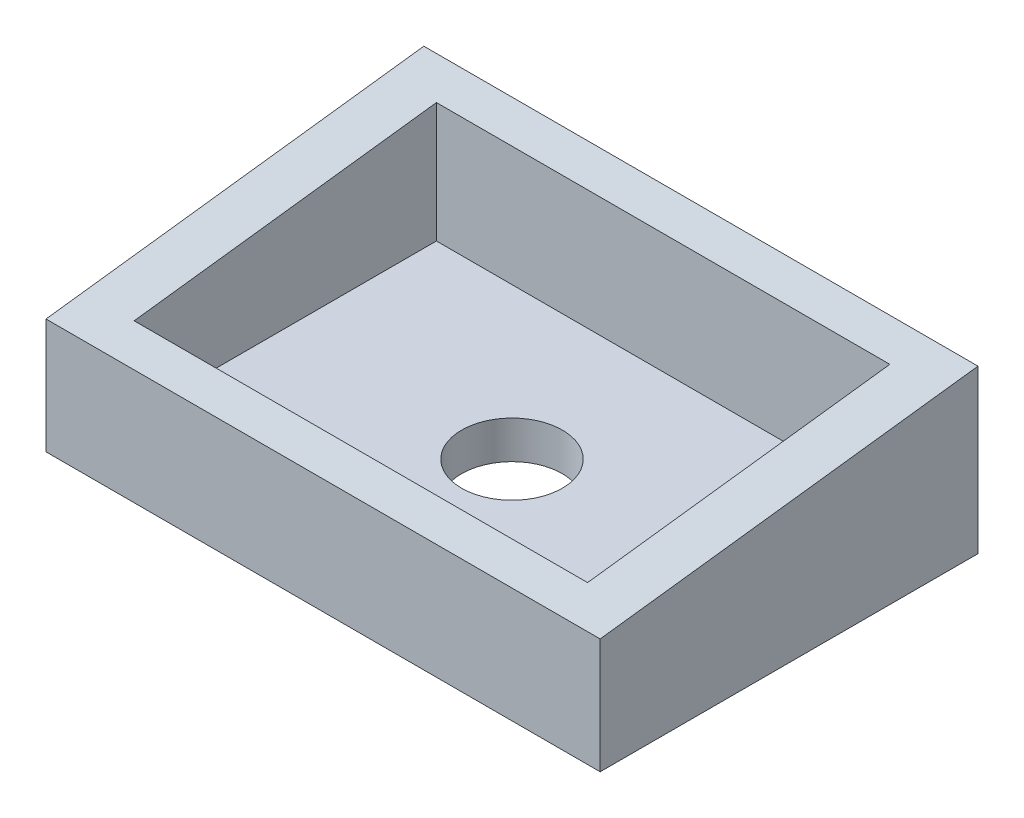
SolidWorks part; units mm, degrees
ref_plane "Front Plane" through (0, 0, 0) normal (0, 0, 1) x (1, 0, 0)
ref_plane "Top Plane" through (0, 0, 0) normal (0, 1, 0) x (1, 0, 0)
ref_plane "Right Plane" through (0, 0, 0) normal (1, 0, 0) x (0, 0, -1)
sketch "Sketch2" plane through (0, 0, 0) normal (0, 1, 0) x (1, 0, 0)
  line L1 (0, 0) -> (22, 0)
  line L2 (0, 0) -> (0, 15)
  line L3 (0, 15) -> (22, 15)
  line L4 (22, 0) -> (22, 15)
  dimension "D1" = 15
  dimension "D2" = 22
extrude "Boss-Extrude1" add sketch "Sketch2" along normal blind 8
ref_plane "Plane1" through (2, 0, 0) normal (1, 0, 0) x (0, 0, -1)
sketch "Sketch6" plane through (2, 0, 0) normal (1, 0, 0) x (0, 0, -1)
  line L0 (-0.5453, 4.5) -> (15.4156, 6.5)
  line L1 (15.4156, 6.5) -> (15.4156, 8.5713)
  line L2 (15.4156, 8.5713) -> (-0.5453, 8.5713)
  line L3 (-0.5453, 8.5713) -> (-0.5453, 4.5)
  line L4 (0, 8) -> (15, 8) construction
  dimension "D1" = 3.5
  dimension "D2" = 1.5
extrude "Cut-Extrude2" cut sketch "Sketch6" along normal through all both and the other way through all
sketch "Sketch7" plane through (2, 0, 0) normal (1, 0, 0) x (0, 0, -1)
  line L0 (1.5, 1.5) -> (13.5, 1.5)
  line L1 (13.5, 1.5) -> (13.5, 6.76)
  line L2 (13.5, 6.76) -> (1.5, 6.76)
  line L3 (1.5, 6.76) -> (1.5, 1.5)
  line L4 (0, 4.5683) -> (0, 0) construction
  line L5 (15, 6.4479) -> (15, 0) construction
  line L6 (0, 0) -> (15, 0) construction
  dimension "D1" = 1.5
  dimension "D2" = 1.5
  dimension "D3" = 1.5
extrude "Cut-Extrude3" cut sketch "Sketch7" along normal blind 18
sketch "Sketch9" plane through (0, 1.5, 0) normal (0, 1, 0) x (1, 0, 0)
  line L0 (22, 15) -> (0, 15) construction
  line L1 (22, 0) -> (22, 15) construction
  circle A0 centre (11, 7.5) radius 2
  dimension "D1" = 7.5
  dimension "D2" = 11
extrude "Cut-Extrude4" cut sketch "Sketch9" against normal through all both and the other way through all
